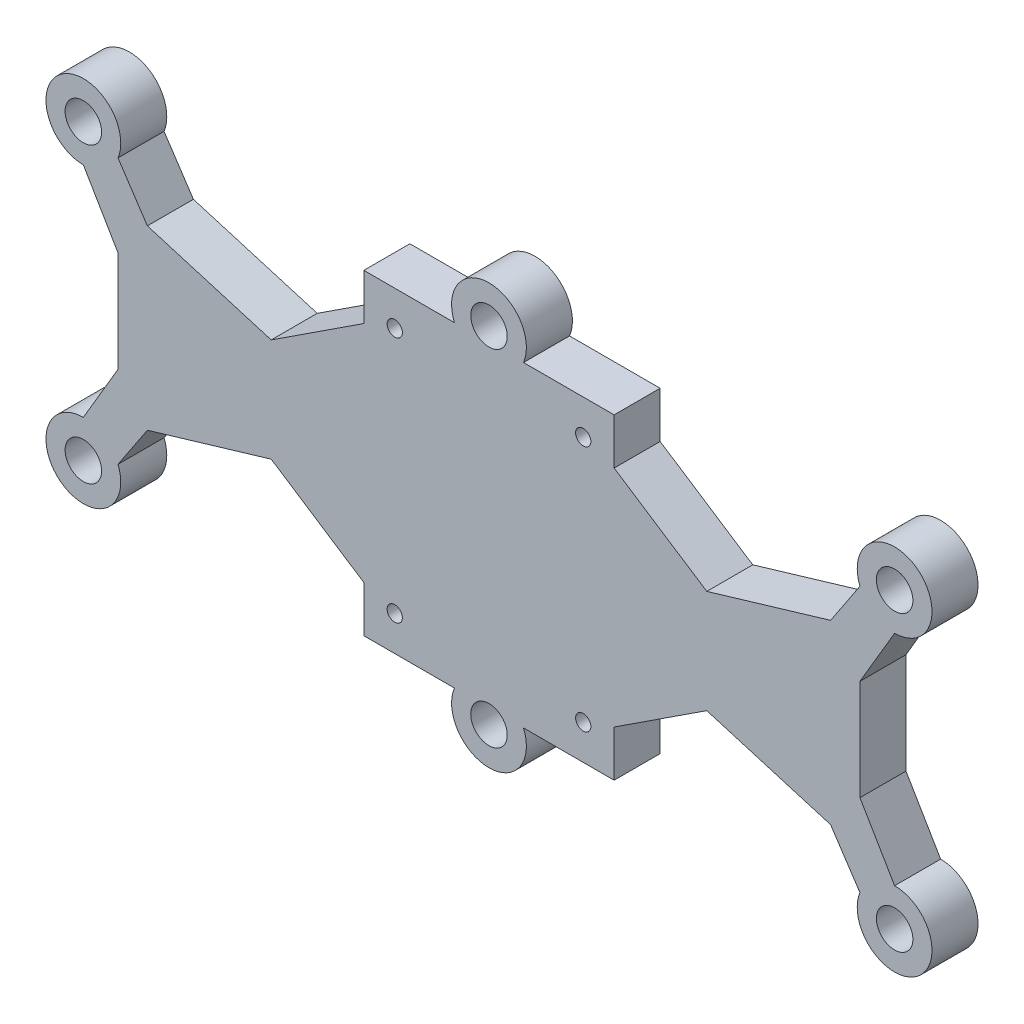
SolidWorks part; units mm, degrees
ref_plane "Front Plane" through (0, 0, 0) normal (0, 0, 1) x (1, 0, 0)
ref_plane "Top Plane" through (0, 0, 0) normal (0, 1, 0) x (1, 0, 0)
ref_plane "Right Plane" through (0, 0, 0) normal (1, 0, 0) x (0, 0, -1)
sketch "Sketch1" plane through (0, 0, 0) normal (0, 0, 1) x (1, 0, 0)
  line L0 (0, 0) -> (52.642, 0) construction
  line L1 (0, 0) -> (0, 40.5761) construction
  line L2 (-21.75, 27.5) -> (-6, 27.5)
  line L3 (21.75, 27.5) -> (21.75, 19.4897)
  line L4 (-21.75, 27.5) -> (-21.75, 19.4897)
  line L5 (-21.75, -27.5) -> (-6, -27.5)
  line L6 (21.75, 19.4897) -> (37.8525, 8.9771)
  line L7 (37.8525, 8.9771) -> (59.3753, 15.3784)
  line L8 (59.3753, 15.3784) -> (64.4769, 23.0563)
  line L9 (21.75, -19.4897) -> (37.8525, -8.9771)
  line L10 (37.8525, -8.9771) -> (59.3753, -15.3784)
  line L11 (59.3753, -15.3784) -> (64.4769, -23.0563)
  line L12 (64.4769, -8.76) -> (64.4769, 8.76)
  line L13 (64.4769, 8.76) -> (70.5, 19)
  line L14 (64.4769, -8.76) -> (70.5, -19)
  line L15 (21.75, -19.4897) -> (21.75, -27.5)
  line L16 (-21.75, -19.4897) -> (-37.8525, -8.9771)
  line L17 (-21.75, 19.4897) -> (-37.8525, 8.9771)
  line L18 (-37.8525, 8.9771) -> (-59.3753, 15.3784)
  line L19 (-37.8525, -8.9771) -> (-59.3753, -15.3784)
  line L20 (-59.3753, -15.3784) -> (-64.4769, -23.0563)
  line L21 (-59.3753, 15.3784) -> (-64.4769, 23.0563)
  line L22 (-64.4769, 8.76) -> (-70.5, 19)
  line L23 (-64.4769, -8.76) -> (-70.5, -19)
  line L24 (-64.4769, -8.76) -> (-64.4769, 8.76)
  line L25 (-21.75, -19.4897) -> (-21.75, -27.5)
  line L26 (6, -27.5) -> (21.75, -27.5)
  line L27 (6, 27.5) -> (21.75, 27.5)
  circle A0 centre (0, 30) radius 3.175
  circle A1 centre (70.5, 25.5) radius 3.175
  circle A2 centre (70.5, -25.5) radius 3.175
  circle A3 centre (0, -30) radius 3.175
  circle A6 centre (-70.5, -25.5) radius 3.175
  circle A7 centre (-70.5, 25.5) radius 3.175
  arc A8 (6, 27.5) -> (-6, 27.5) centre (0, 30) ccw
  circle A9 centre (16.38, 21.46) radius 1.325
  circle A10 centre (-16.38, 21.46) radius 1.325
  circle A11 centre (-16.38, -21.46) radius 1.325
  circle A12 centre (16.38, -21.46) radius 1.325
  arc A13 (70.5, 19) -> (64.4769, 23.0563) centre (70.5, 25.5) ccw
  arc A14 (64.4769, -23.0563) -> (70.5, -19) centre (70.5, -25.5) ccw
  arc A15 (-6, -27.5) -> (6, -27.5) centre (0, -30) ccw
  arc A16 (-64.4769, -23.0563) -> (-70.5, -19) centre (-70.5, -25.5) cw
  arc A17 (-70.5, 19) -> (-64.4769, 23.0563) centre (-70.5, 25.5) cw
  point P22 (0, 24.835)
  point P23 (19.6861, 0)
  point P24 (-19.6861, 0)
  point P48 (64.4769, 0)
  dimension "D2" = 6.35
  dimension "D6" = 2.65
  dimension "D8" = 6.5
  dimension "D1" = 51
  dimension "D3" = 141
  dimension "D4" = 60
  dimension "D5" = 32.76
  dimension "D7" = 42.92
  dimension "D9" = 55
  dimension "D10" = 43.5
extrude "Boss-Extrude1" add sketch "Sketch1" along normal blind 8
